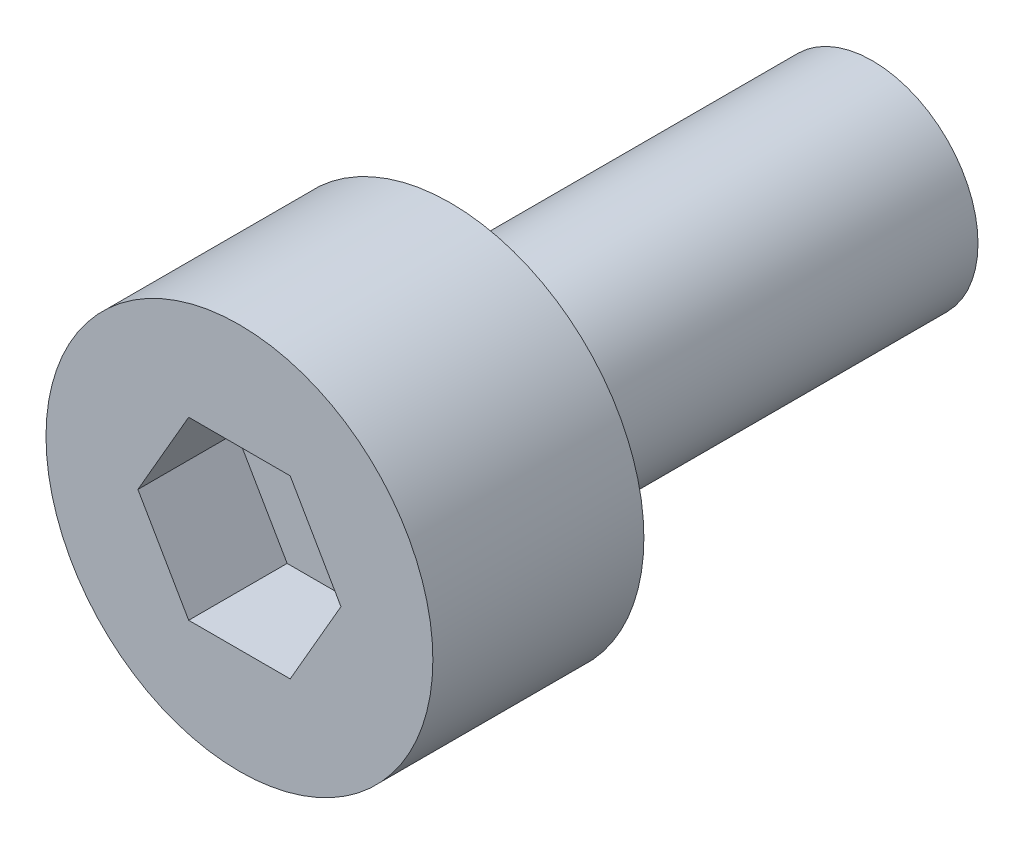
SolidWorks part; units mm, degrees
ref_plane "前视基准面" through (0, 0, 0) normal (0, 0, 1) x (1, 0, 0)
ref_plane "上视基准面" through (0, 0, 0) normal (0, 1, 0) x (1, 0, 0)
ref_plane "右视基准面" through (0, 0, 0) normal (1, 0, 0) x (0, 0, -1)
other "Configuration Table"
sketch "ISO4762_head_D5p5_h3_Sketch" plane through (0, 0, 0) normal (0, 0, 1) x (1, 0, 0)
  circle A0 centre (0, 0) radius 2.75
extrude "ISO4762_head_D5p5_h3" add sketch "ISO4762_head_D5p5_h3_Sketch" along normal blind 3 separate body
sketch "M3_major_diameter_envelope_Sketch" plane through (0, 0, 0) normal (0, 0, 1) x (1, 0, 0)
  circle A0 centre (0, 0) radius 1.5
extrude "M3_major_diameter_envelope" add sketch "M3_major_diameter_envelope_Sketch" along normal blind 6 from offset 6
sketch "Hex_socket_2p5AF_Sketch" plane through (0, 0, 0) normal (0, 0, 1) x (1, 0, 0)
  line L0 (1.4434, 0) -> (0.7217, 1.25)
  line L1 (0.7217, 1.25) -> (-0.7217, 1.25)
  line L2 (-0.7217, 1.25) -> (-1.4434, 0)
  line L3 (-1.4434, 0) -> (-0.7217, -1.25)
  line L4 (-0.7217, -1.25) -> (0.7217, -1.25)
  line L5 (0.7217, -1.25) -> (1.4434, 0)
extrude "Hex_socket_2p5AF" cut sketch "Hex_socket_2p5AF_Sketch" along normal blind 1.4 from offset 1.6
